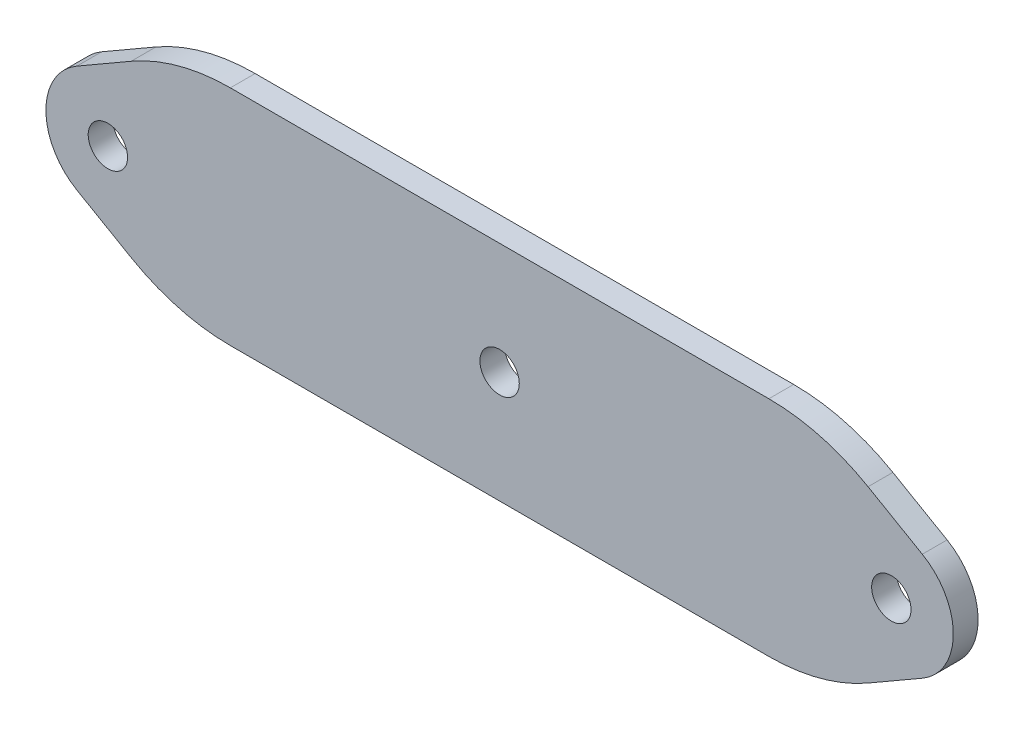
SolidWorks part; units mm, degrees
ref_plane "Front Plane" through (0, 0, 0) normal (0, 0, 1) x (1, 0, 0)
ref_plane "Top Plane" through (0, 0, 0) normal (0, 1, 0) x (1, 0, 0)
ref_plane "Right Plane" through (0, 0, 0) normal (1, 0, 0) x (0, 0, -1)
sketch "Sketch1" plane through (0, 0, 0) normal (0, 0, 1) x (1, 0, 0)
  line L6 (-54.282, 22.5) -> (54.282, 22.5)
  line L7 (74.282, 17.141) -> (85.2211, 10.8253)
  line L8 (85.2211, -10.8253) -> (74.282, -17.141)
  line L9 (54.282, -22.5) -> (-54.282, -22.5)
  line L10 (-74.282, -17.141) -> (-85.2211, -10.8253)
  line L11 (-85.2211, 10.8253) -> (-74.282, 17.141)
  arc A8 (85.2211, -10.8253) -> (85.2211, 10.8253) centre (78.9711, 0) ccw
  arc A9 (-85.2211, -10.8253) -> (-85.2211, 10.8253) centre (-78.9711, 0) cw
  arc A10 (54.282, 22.5) -> (74.282, 17.141) centre (54.282, -17.5) cw
  arc A11 (54.282, -22.5) -> (74.282, -17.141) centre (54.282, 17.5) ccw
  arc A12 (-54.282, -22.5) -> (-74.282, -17.141) centre (-54.282, 17.5) cw
  arc A13 (-74.282, 17.141) -> (-54.282, 22.5) centre (-54.282, -17.5) cw
  circle A14 centre (-78.9711, 0) radius 3.9688
  circle A15 centre (78.9711, 0) radius 3.9688
  circle A16 centre (0, 0) radius 3.9688
  point P10 (9.4242, 3.2242)
  point P14 (103.9711, 0)
  point P17 (-103.9711, 0)
  point P20 (65, 22.5)
  point P24 (65, -22.5)
  point P27 (-65, -22.5)
  point P30 (-65, 22.5)
  dimension "D3" = 60
  dimension "D4" = 65
  dimension "D5" = 65
  dimension "D6" = 22.5
  dimension "D7" = 12.5
  dimension "D8" = 40
  dimension "D9" = 7.9375
  dimension "D10" = 7.9375
  dimension "D11" = 7.9375
  dimension "D1" = 45
  dimension "D2" = 120
extrude "Boss-Extrude2" add sketch "Sketch1" along normal blind 5
